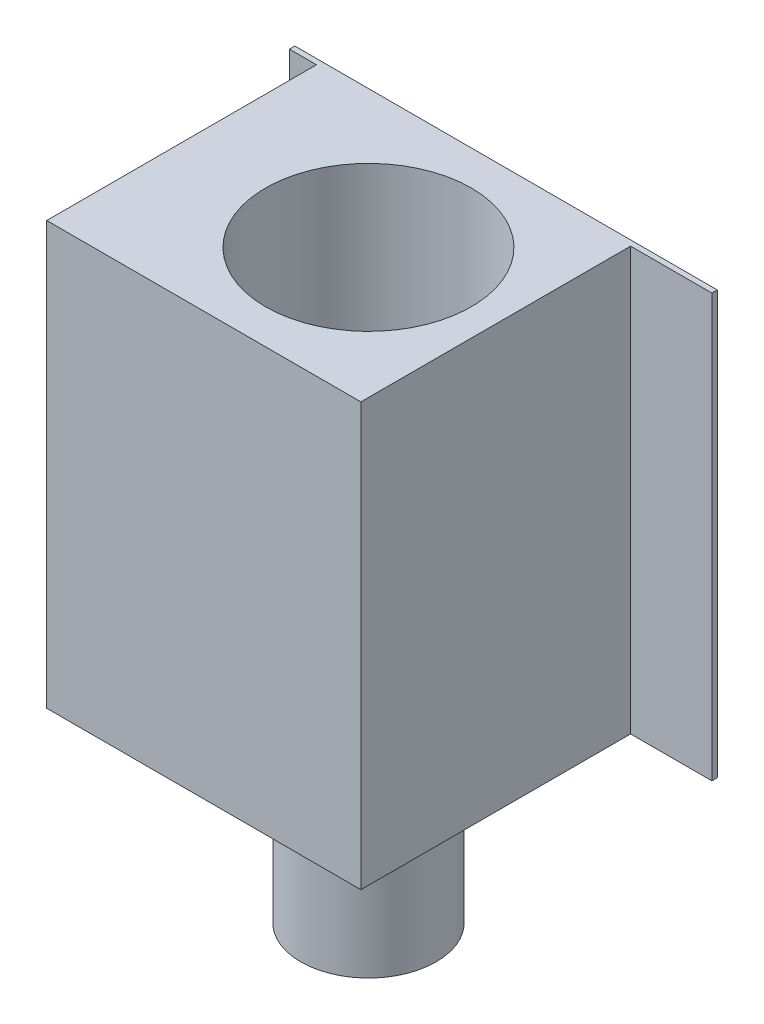
SolidWorks part; units mm, degrees
ref_plane "前视基准面" through (0, 0, 0) normal (0, 0, 1) x (1, 0, 0)
ref_plane "上视基准面" through (0, 0, 0) normal (0, 1, 0) x (1, 0, 0)
ref_plane "右视基准面" through (0, 0, 0) normal (1, 0, 0) x (0, 0, -1)
sketch "草图1" plane through (0, 0, 0) normal (0, 1, 0) x (1, 0, 0)
  line L0 (0, 11.3571) -> (0, -8.6742) construction
  line L1 (-3.9, 2.54) -> (3.9, 2.54)
  line L2 (-3.9, 2.54) -> (-3.9, -2.54)
  line L3 (-3.9, -2.54) -> (3.9, -2.54)
  line L4 (3.9, 2.54) -> (3.9, -2.54)
  line L5 (-11.8577, 0) -> (16.1453, 0) construction
  dimension "D1" = 7.8
  dimension "D2" = 5.08
extrude "拉伸1" add sketch "草图1" along normal blind 7.8
sketch "草图2" plane through (0, 7.8, 0) normal (0, 1, 0) x (1, 0, 0)
  line L0 (-4.7448, 0) -> (6.3035, 0) construction
  line L1 (0, 3.5336) -> (0, -3.8045) construction
  circle A0 centre (0, 0) radius 1.9
  dimension "D1" = 3.8
extrude "切除-拉伸1" cut sketch "草图2" against normal blind 4.2
sketch "草图3" plane through (0, 3.6, 0) normal (0, 1, 0) x (1, 0, 0)
  line L0 (-1.6579, 0) -> (1.776, 0) construction
  line L1 (-1.2545, 0.3075) -> (1.2545, 0.3075)
  line L2 (-1.2545, 0.3075) -> (-1.2545, -0.3075)
  line L3 (-1.2545, -0.3075) -> (1.2545, -0.3075)
  line L4 (1.2545, 0.3075) -> (1.2545, -0.3075)
  line L5 (0, 0.9913) -> (0, -0.7699) construction
extrude "切除-拉伸2" cut sketch "草图3" against normal blind 0.5
sketch "草图4" plane through (0, 0, 0) normal (0, -1, 0) x (1, 0, 0)
  circle A0 centre (0, 0) radius 1.25
  dimension "D1" = 2.5
extrude "凸台-拉伸1" add sketch "草图4" along normal blind 3
sketch "草图5" plane through (0, 7.8, 0) normal (0, 1, 0) x (1, 0, 0)
  line L0 (-3.9, 2.54) -> (-3.9, -2.54) construction
  line L1 (-3.9, 2.44) -> (-3.4, 2.44)
  line L2 (-3.9, 2.44) -> (-3.9, -2.54)
  line L3 (-3.9, -2.54) -> (-3.4, -2.54)
  line L4 (-3.4, 2.44) -> (-3.4, -2.54)
  line L5 (-3.9, -2.54) -> (3.9, -2.54) construction
  line L7 (3.9, 2.54) -> (-3.9, 2.54) construction
  line L9 (3.9, -2.54) -> (2.4, -2.54)
  line L10 (3.9, -2.54) -> (3.9, 2.44)
  line L11 (3.9, 2.44) -> (2.4, 2.44)
  line L12 (2.4, -2.54) -> (2.4, 2.44)
  dimension "D1" = 0.5
  dimension "D2" = 0.1
  dimension "D3" = 5.8
extrude "切除-拉伸3" cut sketch "草图5" against normal through all
